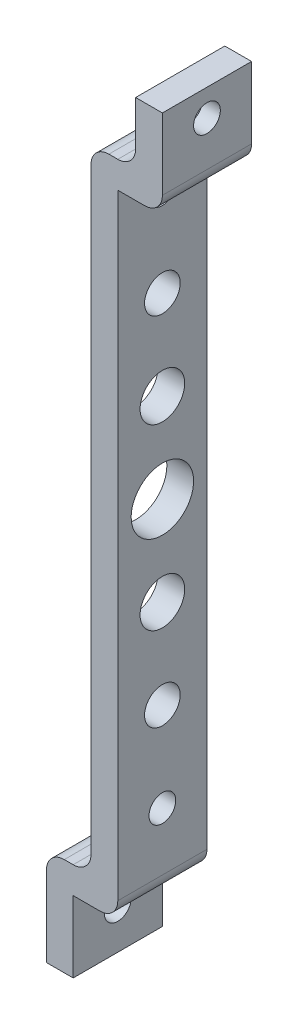
SolidWorks part; units mm, degrees
ref_plane "Ön Düzlem" through (0, 0, 0) normal (0, 0, 1) x (1, 0, 0)
ref_plane "Üst Düzlem" through (0, 0, 0) normal (0, 1, 0) x (1, 0, 0)
ref_plane "Sağ Düzlem" through (0, 0, 0) normal (1, 0, 0) x (0, 0, -1)
sketch "Çizim1" plane through (0, 0, 0) normal (0, 0, 1) x (1, 0, 0)
  line L0 (10, 87) -> (10, 81)
  line L1 (10, 81) -> (5, 81)
  line L2 (5, 81) -> (5, 10)
  line L3 (13, 87) -> (13, 78)
  line L4 (13, 78) -> (8, 78)
  line L5 (8, 78) -> (8, 7)
  line L7 (10, 87) -> (13, 87)
  line L8 (5, 10) -> (0, 10)
  line L9 (0, 10) -> (0, 0)
  line L10 (0, 0) -> (3, 0)
  line L11 (3, 0) -> (3, 7)
  line L12 (3, 7) -> (8, 7)
  line L14 (8, 78) -> (8, -31) construction
  line L16 (5, 81) -> (5, -31) construction
  dimension "D1" = 5
  dimension "D2" = 6
  dimension "D3" = 5
  dimension "D5" = 3
  dimension "D6" = 71
  dimension "D7" = 3
  dimension "D8" = 87
  dimension "D4" = 3
extrude "Yükseklik-Ekstrüzyon1" add sketch "Çizim1" along normal blind 10
sketch "Çizim2" plane through (0, 87, 0) normal (0, 1, 0) x (1, 0, 0)
  line L4 (13, 0) -> (10, 0)
  line L5 (10, 0) -> (10, -10)
  line L6 (10, -10) -> (13, -10)
  line L7 (13, -10) -> (13, 0)
  line L8 (13, 0) -> (10, 0)
  line L9 (10, 0) -> (10, -10)
  line L10 (10, -10) -> (13, -10)
  line L11 (13, -10) -> (13, 0)
  dimension "D1" = 0
extrude "Yükseklik-Ekstrüzyon2" add sketch "Çizim2" along normal blind 1
sketch "Çizim3" plane through (0, 0, 0) normal (0, -1, 0) x (1, 0, 0)
  line L4 (0, 0) -> (3, 0)
  line L5 (3, 0) -> (3, 10)
  line L6 (3, 10) -> (0, 10)
  line L7 (0, 10) -> (0, 0)
  line L8 (0, 0) -> (3, 0)
  line L9 (3, 0) -> (3, 10)
  line L10 (3, 10) -> (0, 10)
  line L11 (0, 10) -> (0, 0)
  dimension "D1" = 0
extrude "Yükseklik-Ekstrüzyon3" add sketch "Çizim3" along normal blind 1
sketch "Çizim4" plane through (10, 0, 0) normal (-1, 0, 0) x (0, 0, 1)
  line L0 (5, 88) -> (5, 83.1974) construction
  line L1 (0, 88) -> (10, 88) construction
  circle A0 centre (5, 85) radius 3 construction
  circle A1 centre (5, 85) radius 1.5
  dimension "D1" = 6
  dimension "D2" = 3
extrude "Kes-Ekstrüzyon1" cut sketch "Çizim4" against normal blind 4
chamfer "Pah1" distance 1 angle 45 1 edges at (10, 83.5, 5)
sketch "Çizim5" plane through (0, 0, 0) normal (-1, 0, 0) x (0, 0, 1)
  line L0 (5, -1) -> (5, 8) construction
  line L1 (10, -1) -> (0, -1) construction
  circle A0 centre (5, 3.5) radius 4.5 construction
  circle A1 centre (5, 3.5) radius 1.5
  dimension "D1" = 4.5
  dimension "D2" = 3
extrude "Kes-Ekstrüzyon2" cut sketch "Çizim5" against normal blind 4
chamfer "Pah2" distance 1 angle 45 1 edges at (0, 2, 5)
fillet "Radyus1" radius 2 6 edges at (5, 81, 5) (10, 81, 5) (13, 78, 5) (8, 7, 5) (0, 10, 5) (5, 10, 5)
sketch "Çizim6" plane through (5, 0, 0) normal (-1, 0, 0) x (0, 0, 1)
  line L0 (5, 79) -> (5, 12) construction
  line L1 (10, 79) -> (0, 79) construction
  line L2 (0, 12) -> (10, 12) construction
  line L3 (5, 45.5) -> (-27.6631, 45.5) construction
  circle A0 centre (5, 45.5) radius 3.5
  circle A1 centre (5, 55.5) radius 2.5
  circle A2 centre (5, 65.5) radius 2
  circle A3 centre (5, 75.5) radius 1.5
  circle A4 centre (5, 15.5) radius 1.5
  circle A5 centre (5, 25.5) radius 2
  circle A6 centre (5, 35.5) radius 2.5
  dimension "D1" = 7
  dimension "D2" = 5
  dimension "D3" = 4
  dimension "D4" = 3
  dimension "D5" = 10
  dimension "D6" = 10
  dimension "D7" = 10
extrude "Kes-Ekstrüzyon3" cut sketch "Çizim6" against normal blind 4
